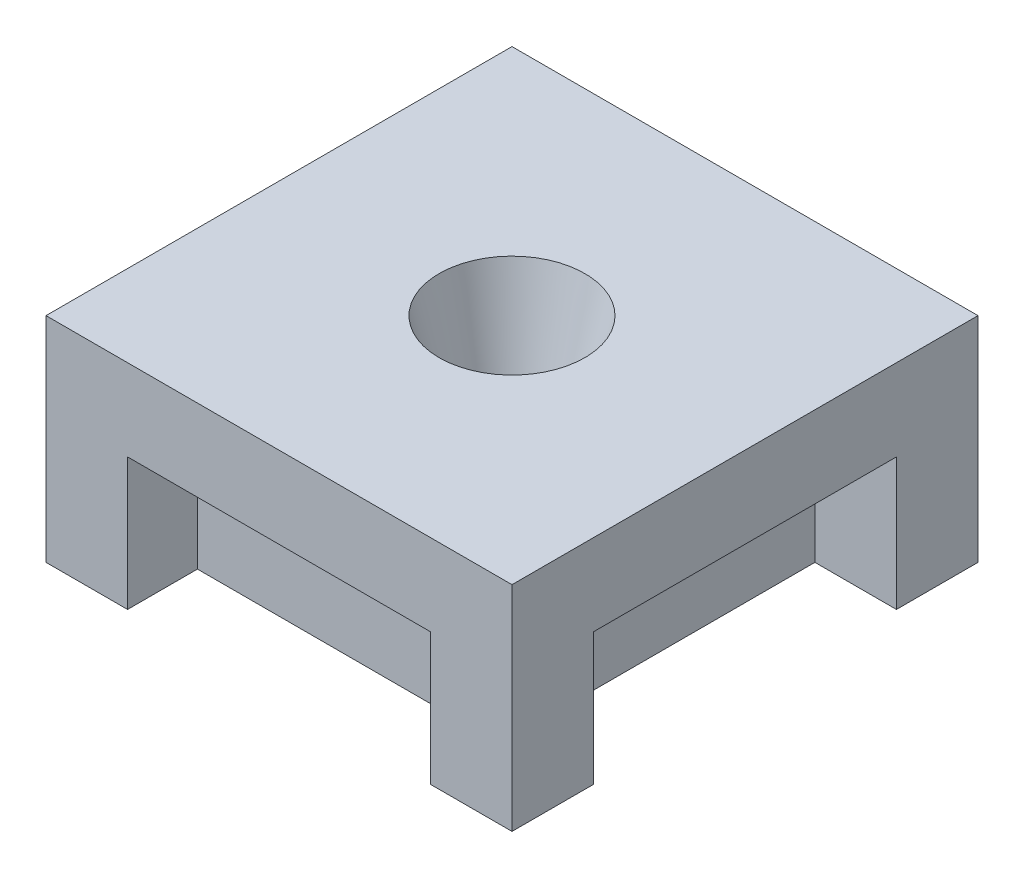
SolidWorks part; units mm, degrees
ref_plane "Plano frontal" through (0, 0, 0) normal (0, 0, 1) x (1, 0, 0)
ref_plane "Plano superior" through (0, 0, 0) normal (0, 1, 0) x (1, 0, 0)
ref_plane "Plano direito" through (0, 0, 0) normal (1, 0, 0) x (0, 0, -1)
sketch "Esboço1" plane through (0, 0, 0) normal (0, 1, 0) x (1, 0, 0)
  line L1 (-33.7032, -8.1007) -> (6.2968, -8.1007)
  line L2 (-33.7032, -8.1007) -> (-33.7032, -48.1007)
  line L3 (-33.7032, -48.1007) -> (6.2968, -48.1007)
  line L4 (6.2968, -8.1007) -> (6.2968, -48.1007)
extrude "Ressalto-extrusão1" add sketch "Esboço1" along normal blind 40
sketch "Esboço2" plane through (0, 40, 0) normal (0, 1, 0) x (1, 0, 0)
  line L0 (6.2968, -8.1007) -> (-33.7032, -8.1007) construction
  line L1 (6.2968, -48.1007) -> (6.2968, -8.1007) construction
  circle A0 centre (-13.7032, -28.1007) radius 6.255
  dimension "D1" = 20
  dimension "D2" = 20
  dimension "D3" = 12.51
ref_plane "Plano1" through (0, 24.13, 0) normal (0, 1, 0) x (1, 0, 0)
sketch "Esboço4" plane through (0, 24.13, 0) normal (0, 1, 0) x (1, 0, 0)
  line L0 (6.2968, -8.1007) -> (-33.7032, -8.1007) construction
  line L1 (-33.7032, -8.1007) -> (-33.7032, -48.1007) construction
  circle A0 centre (-13.7032, -28.1007) radius 2.41
  circle A1 centre (-13.7032, -28.1007) radius 6.255 construction
  dimension "D1" = 4.82
sketch "Esboço10" plane through (-33.7032, 0, 0) normal (-1, 0, 0) x (0, 0, 1)
  line L1 (41.1007, 33) -> (15.1007, 33)
  line L2 (41.1007, 33) -> (41.1007, 7)
  line L3 (41.1007, 7) -> (15.1007, 7)
  line L4 (15.1007, 33) -> (15.1007, 7)
  line L5 (8.1007, 0) -> (48.1007, 0) construction
  line L6 (48.1007, 40) -> (48.1007, 0) construction
  line L7 (8.1007, 40) -> (8.1007, 0) construction
  dimension "D2" = 7
  dimension "D3" = 7
  dimension "D4" = 7
extrude "Corte-extrusão3" cut sketch "Esboço10" against normal blind 7
sketch "Esboço11" plane through (0, 0, 8.1007) normal (0, 0, -1) x (-1, 0, 0)
  line L0 (-6.2968, 40) -> (-6.2968, 0) construction
  line L1 (0.7032, 33) -> (26.7032, 33)
  line L2 (0.7032, 33) -> (0.7032, 7)
  line L3 (0.7032, 7) -> (26.7032, 7)
  line L4 (26.7032, 33) -> (26.7032, 7)
  line L5 (33.7032, 40) -> (33.7032, 0) construction
  line L7 (-6.2968, 0) -> (33.7032, 0) construction
  dimension "D1" = 7
  dimension "D2" = 7
  dimension "D4" = 7
extrude "Corte-extrusão6" cut sketch "Esboço11" against normal blind 6
sketch "Esboço12" plane through (0, 0, 48.1007) normal (0, 0, 1) x (1, 0, 0)
  line L0 (-33.7032, 40) -> (-33.7032, 0) construction
  line L1 (-26.7032, 33) -> (-0.7032, 33)
  line L2 (-26.7032, 33) -> (-26.7032, 7)
  line L3 (-26.7032, 7) -> (-0.7032, 7)
  line L4 (-0.7032, 33) -> (-0.7032, 7)
  line L6 (6.2968, 40) -> (6.2968, 0) construction
  line L7 (-33.7032, 0) -> (6.2968, 0) construction
  dimension "D1" = 7
  dimension "D3" = 7
  dimension "D4" = 7
extrude "Corte-extrusão7" cut sketch "Esboço12" against normal blind 6
sketch "Esboço13" plane through (6.2968, 0, 0) normal (1, 0, 0) x (0, 0, -1)
  line L1 (-41.1007, 33) -> (-15.1007, 33)
  line L2 (-41.1007, 33) -> (-41.1007, 7)
  line L3 (-41.1007, 7) -> (-15.1007, 7)
  line L4 (-15.1007, 33) -> (-15.1007, 7)
  line L5 (-48.1007, 40) -> (-48.1007, 0) construction
  line L6 (-48.1007, 0) -> (-8.1007, 0) construction
  line L7 (-8.1007, 40) -> (-8.1007, 0) construction
  dimension "D2" = 7
  dimension "D3" = 7
  dimension "D4" = 7
extrude "Corte-extrusão8" cut sketch "Esboço13" against normal blind 7
loft "Loft de corte2" cut profiles "Esboço2", "Esboço4"
fillet "Filete2" radius 0.5 1 edges at (-13.7032, 24.13, 30.5107)
sketch "Esboço14" plane through (0, 0, 14.1007) normal (0, 0, -1) x (-1, 0, 0)
  line L0 (-6.2968, 40) -> (-6.2968, 0) construction
  line L1 (33.7032, 0) -> (-6.2968, 0)
  line L2 (33.7032, 0) -> (33.7032, 21.6556)
  line L3 (33.7032, 21.6556) -> (-6.2968, 21.6556)
  line L4 (-6.2968, 0) -> (-6.2968, 21.6556)
extrude "Corte-extrusão9" cut sketch "Esboço14" against normal blind 37 and the other way blind 37
